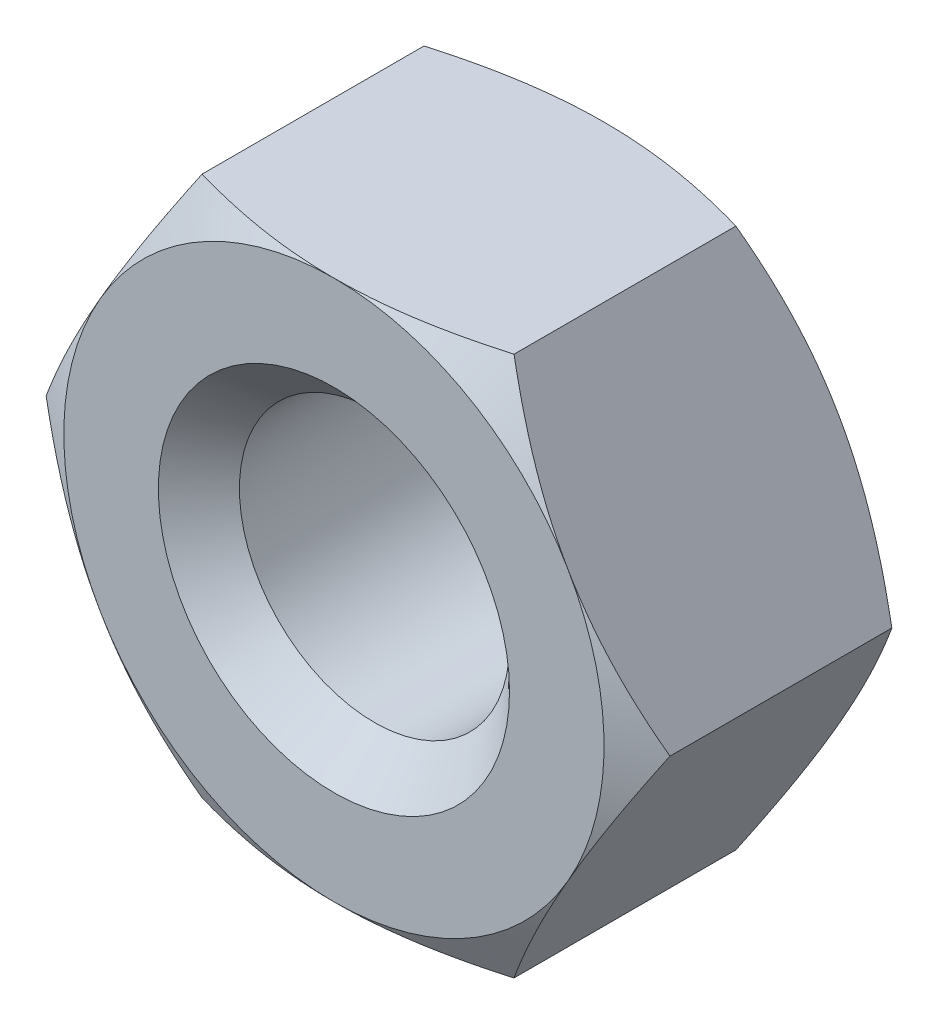
SolidWorks part; units mm, degrees
material "Простая углеродистая сталь"
ref_plane "Спереди" through (0, 0, 0) normal (0, 0, 1) x (1, 0, 0)
ref_plane "Сверху" through (0, 0, 0) normal (0, 1, 0) x (1, 0, 0)
ref_plane "Справа" through (0, 0, 0) normal (1, 0, 0) x (0, 0, -1)
sketch "Эскиз1" plane through (0, 0, 0) normal (0, 0, 1) x (1, 0, 0)
  line L1 (4.6188, 0) -> (2.3094, 4)
  line L2 (2.3094, 4) -> (-2.3094, 4)
  line L3 (-2.3094, 4) -> (-4.6188, 0)
  line L4 (-4.6188, 0) -> (-2.3094, -4)
  line L5 (-2.3094, -4) -> (2.3094, -4)
  line L6 (2.3094, -4) -> (4.6188, 0)
  circle A0 centre (0, 0) radius 4 construction
  circle A1 centre (0, 0) radius 2
  dimension "D2" = 4
  dimension "D1" = 8
extrude "Бобышка-Вытянуть1" add sketch "Эскиз1" along normal blind 4
cosmetic thread "Условное изображение резьбы1" parameters "D1"=4, "D2"=5
sketch "Эскиз2" plane through (0, 0, 0) normal (0, 0, -1) x (-1, 0, 0)
  line L0 (-2.3094, 4) -> (2.3094, 4) construction
  circle A0 centre (0, 0) radius 4
extrude "Вырез-Вытянуть2" cut sketch "Эскиз2" against normal blind 4 draft 60 flip side to cut contours A0
sketch "Эскиз3" plane through (0, 0, 4) normal (0, 0, 1) x (1, 0, 0)
  line L0 (2.3094, -4) -> (4.6188, 0) construction
  circle A0 centre (0, 0) radius 4
extrude "Вырез-Вытянуть3" cut sketch "Эскиз3" against normal blind 4 draft 60 flip side to cut contours A0
chamfer "Фаска5" distance 0.6 angle 45 2 edges at (2, 0, 4) (2, 0, 0)
